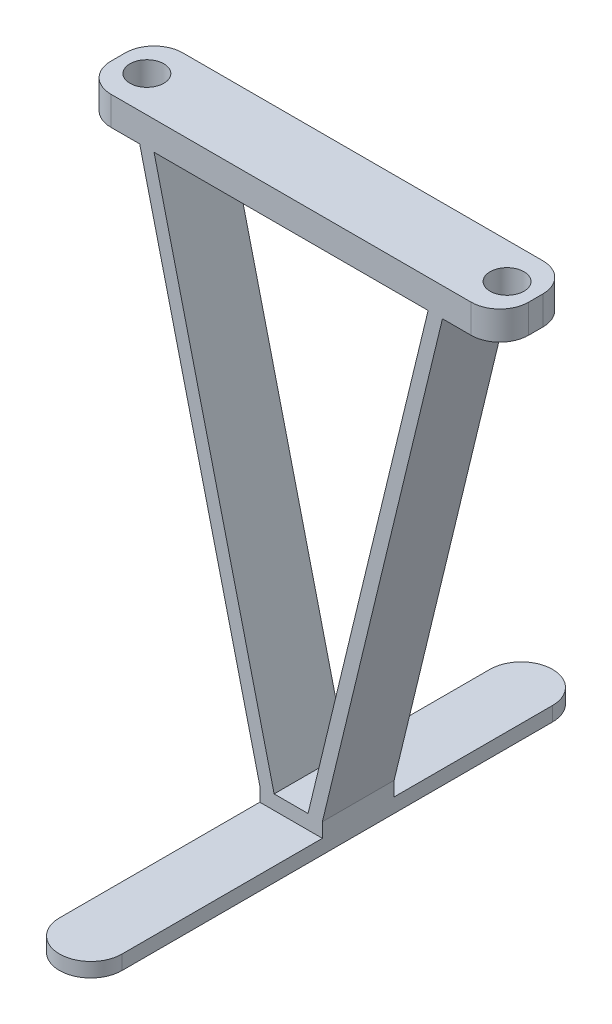
SolidWorks part; units mm, degrees
ref_plane "Front Plane" through (0, 0, 0) normal (0, 0, 1) x (1, 0, 0)
ref_plane "Top Plane" through (0, 0, 0) normal (0, 1, 0) x (1, 0, 0)
ref_plane "Right Plane" through (0, 0, 0) normal (1, 0, 0) x (0, 0, -1)
sketch "Sketch1" plane through (0, 0, 0) normal (0, 1, 0) x (1, 0, 0)
  line L0 (-30.3998, 0) -> (33.3542, 0) construction
  line L1 (1.4772, 0) -> (1.4772, 15.7854) construction
  line L2 (-24.7476, 6.35) -> (-30.3998, 6.35)
  line L4 (-24.7476, -6.35) -> (-30.3998, -6.35)
  line L5 (-35.4798, 1.27) -> (-35.4798, -1.27)
  line L6 (-24.7476, 6.35) -> (27.702, 6.35)
  line L7 (-24.7476, -6.35) -> (27.702, -6.35)
  line L8 (27.702, 6.35) -> (33.3542, 6.35)
  line L9 (38.4342, 1.27) -> (38.4342, -1.27)
  line L10 (27.702, -6.35) -> (33.3542, -6.35)
  circle A0 centre (-30.3998, 0) radius 3
  circle A1 centre (33.3542, 0) radius 3
  arc A2 (33.3542, 6.35) -> (38.4342, 1.27) centre (33.3542, 1.27) cw
  arc A3 (38.4342, -1.27) -> (33.3542, -6.35) centre (33.3542, -1.27) cw
  arc A4 (-35.4798, -1.27) -> (-30.3998, -6.35) centre (-30.3998, -1.27) ccw
  arc A5 (-35.4798, 1.27) -> (-30.3998, 6.35) centre (-30.3998, 1.27) cw
  point P14 (1.4772, 6.35)
  point P17 (1.4772, -6.35)
  point P19 (38.4342, 6.35)
  point P22 (38.4342, -6.35)
  point P25 (-35.4798, -6.35)
  point P28 (-35.4798, 6.35)
  dimension "D2" = 6
  dimension "D3" = 6
  dimension "D5" = 6.35
  dimension "D7" = 5.08
  dimension "D1" = 63.754
  dimension "D4" = 6.35
  dimension "D6" = 5.08
extrude "Boss-Extrude1" add sketch "Sketch1" along normal blind 5.08
sketch "Sketch3" plane through (0, 0, 6.35) normal (0, 0, 1) x (1, 0, 0)
  line L0 (-25.3198, 0) -> (-4.0628, -87.7432)
  line L1 (-30.3998, 0) -> (33.3542, 0) construction
  line L2 (-30.3998, 5.08) -> (-30.3998, 0) construction
  line L3 (1.4772, 5.08) -> (1.4772, -90.2832) construction
  line L4 (-30.3998, 5.08) -> (33.3542, 5.08) construction
  line L5 (-22.7798, 0) -> (-1.5228, -87.7432)
  line L6 (4.4772, -87.7432) -> (-1.5228, -87.7432)
  line L7 (7.0172, -87.7432) -> (7.0172, -90.2832)
  line L8 (7.0172, -90.2832) -> (-4.0628, -90.2832)
  line L9 (-4.0628, -87.7432) -> (-4.0628, -90.2832)
  line L10 (-25.3198, 0) -> (-22.7798, 0)
  line L11 (28.2742, 0) -> (25.7342, 0)
  line L12 (28.2742, 0) -> (7.0172, -87.7432)
  line L13 (25.7342, 0) -> (4.4772, -87.7432)
  dimension "D1" = 5.08
  dimension "D2" = 11.08
  dimension "D3" = 2.54
  dimension "D4" = 2.54
  dimension "D5" = 2.54
extrude "Boss-Extrude2" add sketch "Sketch3" against normal blind 12.7
sketch "Sketch4" plane through (0, -90.2832, 0) normal (0, -1, 0) x (1, 0, 0)
  line L0 (-4.0628, 41.8087) -> (-4.0628, -34.3913)
  line L1 (-4.0628, -6.35) -> (-4.0628, 6.35) construction
  line L2 (7.0172, 41.8087) -> (7.0172, -34.3913)
  line L3 (7.0172, -6.35) -> (7.0172, 6.35) construction
  arc A0 (-4.0628, 41.8087) -> (7.0172, 41.8087) centre (1.4772, 41.8087) cw
  arc A1 (-4.0628, -34.3913) -> (7.0172, -34.3913) centre (1.4772, -34.3913) ccw
  dimension "D1" = 0
  dimension "D2" = 76.2
extrude "Boss-Extrude3" add sketch "Sketch4" along normal blind 2.54
